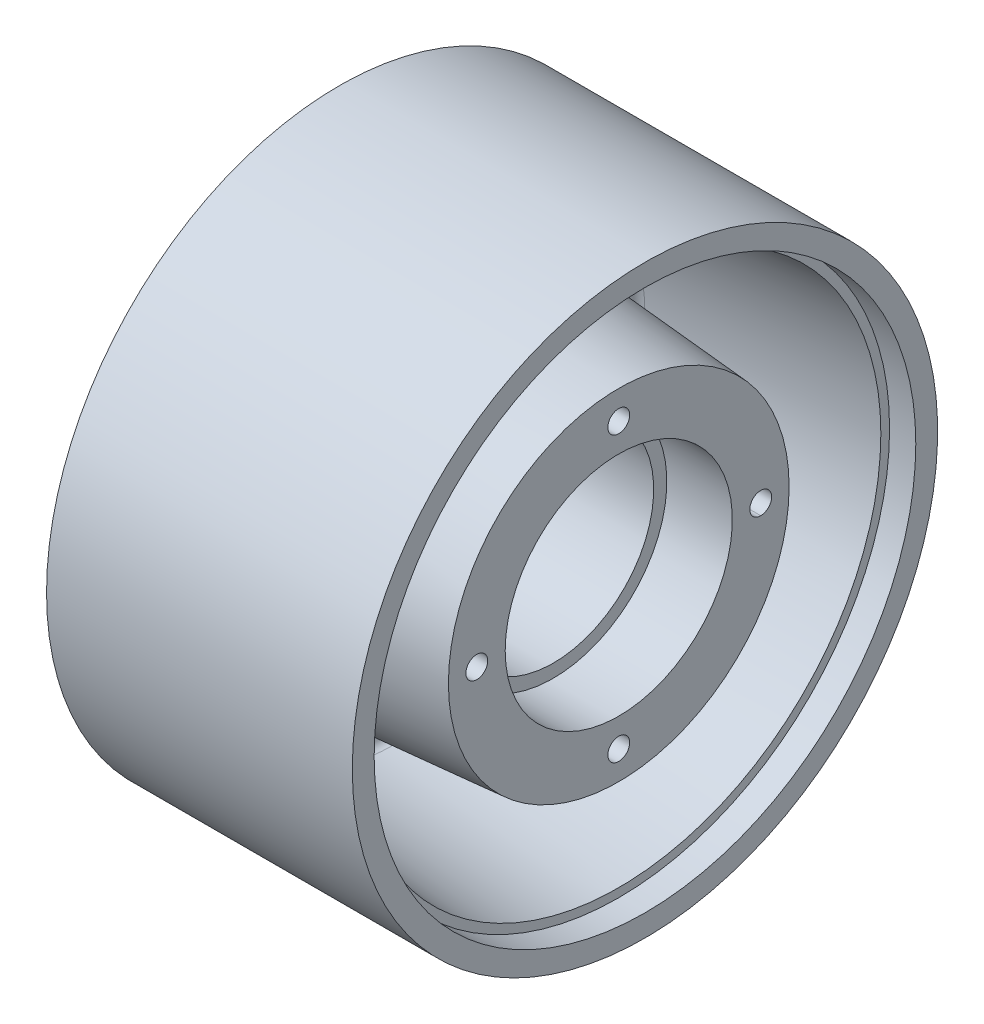
SolidWorks part; units mm, degrees
ref_plane "Alzado" through (0, 0, 0) normal (0, 0, 1) x (1, 0, 0)
ref_plane "Planta" through (0, 0, 0) normal (0, 1, 0) x (1, 0, 0)
ref_plane "Vista lateral" through (0, 0, 0) normal (1, 0, 0) x (0, 0, -1)
sketch "Croquis1" plane through (0, 0, 0) normal (0, 0, 1) x (1, 0, 0)
  line L0 (-33.5155, 0) -> (-7.5155, 0) construction
  line L18 (0, 67) -> (70, 67)
  line L19 (70, 67) -> (70, 62)
  line L20 (70, 62) -> (64, 62)
  line L21 (64, 62) -> (64, 60)
  line L22 (64, 60) -> (12, 56)
  line L23 (12, 56) -> (12, 43)
  line L24 (12, 43) -> (64, 39)
  line L25 (64, 39) -> (64, 26)
  line L27 (25, 26) -> (25, 23)
  line L28 (25, 23) -> (49, 23)
  line L29 (49, 23) -> (49, 26)
  line L31 (10, 26) -> (10, 40)
  line L32 (10, 40) -> (0, 40)
  line L33 (0, 40) -> (0, 67)
  line L34 (130.0302, 49.5) -> (-54.6416, 49.5) construction
  line L35 (10, 26) -> (25, 26)
  line L36 (49, 26) -> (64, 26)
  point P26 (-20.5155, 0)
  dimension "D1" = 67
  dimension "D2" = 62
  dimension "D3" = 60
  dimension "D4" = 15
  dimension "D5" = 23
  dimension "D6" = 15
  dimension "D7" = 70
  dimension "D8" = 6
  dimension "D9" = 54
  dimension "D10" = 12
  dimension "D11" = 40
  dimension "D12" = 3
  dimension "D13" = 39
  dimension "D14" = 13
  dimension "D15" = 3
revolve "Revolución1" add sketch "Croquis1" angle 360 about L0
fillet "Redondeo1" radius 2 2 edges at (12, 0, 43) (12, 0, 56)
hole_wizard "Taladro roscado M64" positions "Croquis15" profile "Croquis16" tap size "M6" standard "DIN"
sketch "Croquis15" plane through (64, 0, 0) normal (1, 0, 0) x (0, 0, -1)
  line L0 (0, 0) -> (0, 86.3628)
  circle A4 centre (0, 0) radius 32.5
  point P0 (0, 32.5)
sketch "Croquis16" plane through (64, 32.5, 0) normal (0, 1, 0) x (0, 0, -1)
  line L0 (0, 0) -> (0, 19.5022)
  line L1 (0, 19.5022) -> (2.5, 18)
  line L2 (2.5, 18) -> (2.5, 0)
  line L5 (2.5, 0) -> (0, 0)
  line L10 (0, 19.5022) -> (-2.5, 18) construction
  line L11 (0, -6.35) -> (0, 107.95) construction
  dimension "Diámetro de perforador para roscar" = 5
  dimension "Profundidad de perforador para roscar" = 18
  dimension "Ángulo de perforador" = 118
cosmetic thread "Rosca de taladro6" parameters "D1"=15, "D2"=6
hole_wizard "Taladro roscado M69" positions "Croquis25" profile "Croquis26" tap size "M6" standard "DIN"
sketch "Croquis25" plane through (64, 0, 0) normal (1, 0, 0) x (0, 0, -1)
  line L0 (0, 0) -> (0, -74.9026)
  circle A1 centre (0, 0) radius 32.5
  point P0 (0, -32.4706)
sketch "Croquis26" plane through (64, -32.4706, 0) normal (0, 1, 0) x (0, 0, -1)
  line L0 (0, 0) -> (0, 19.5022)
  line L1 (0, 19.5022) -> (2.5, 18)
  line L2 (2.5, 18) -> (2.5, 0)
  line L5 (2.5, 0) -> (0, 0)
  line L10 (0, 19.5022) -> (-2.5, 18) construction
  line L11 (0, -6.35) -> (0, 107.95) construction
  dimension "Diámetro de perforador para roscar" = 5
  dimension "Profundidad de perforador para roscar" = 18
  dimension "Ángulo de perforador" = 118
cosmetic thread "Rosca de taladro11" parameters "D1"=15, "D2"=6
hole_wizard "Taladro roscado M611" positions "Croquis29" profile "Croquis30" tap size "M6" standard "DIN"
sketch "Croquis29" plane through (10, 0, 0) normal (-1, 0, 0) x (0, 0, 1)
  line L0 (0, 0) -> (0, 69.3611)
  circle A0 centre (0, 0) radius 32.5
  point P0 (0, 32.4982)
sketch "Croquis30" plane through (10, 32.4982, 0) normal (0, 1, 0) x (0, 0, 1)
  line L0 (0, 0) -> (0, 16.5022)
  line L1 (0, 16.5022) -> (2.5, 15)
  line L2 (2.5, 15) -> (2.5, 0)
  line L5 (2.5, 0) -> (0, 0)
  line L10 (0, 16.5022) -> (-2.5, 15) construction
  line L11 (0, -6.35) -> (0, 107.95) construction
  dimension "Diámetro de perforador para roscar" = 5
  dimension "Profundidad de perforador para roscar" = 15
  dimension "Ángulo de perforador" = 118
cosmetic thread "Rosca de taladro13" parameters "D1"=12, "D2"=6
hole_wizard "Taladro roscado M612" positions "Croquis31" profile "Croquis32" tap size "M6" standard "DIN"
sketch "Croquis31" plane through (10, 0, 0) normal (-1, 0, 0) x (0, 0, 1)
  line L0 (0, 0) -> (0, -90.6399)
  circle A0 centre (0, 0) radius 32.5
  point P0 (0, -32.5002)
sketch "Croquis32" plane through (10, -32.5002, 0) normal (0, 1, 0) x (0, 0, 1)
  line L0 (0, 0) -> (0, 16.5022)
  line L1 (0, 16.5022) -> (2.5, 15)
  line L2 (2.5, 15) -> (2.5, 0)
  line L5 (2.5, 0) -> (0, 0)
  line L10 (0, 16.5022) -> (-2.5, 15) construction
  line L11 (0, -6.35) -> (0, 107.95) construction
  dimension "Diámetro de perforador para roscar" = 5
  dimension "Profundidad de perforador para roscar" = 15
  dimension "Ángulo de perforador" = 118
cosmetic thread "Rosca de taladro14" parameters "D1"=12, "D2"=6
hole_wizard "Taladro roscado M613" positions "Croquis33" profile "Croquis34" tap size "M6" standard "AS"
sketch "Croquis33" plane through (64, 0, 0) normal (1, 0, 0) x (0, 0, -1)
  line L0 (0, 0) -> (100.6706, 0)
  circle A0 centre (0, 0) radius 32.5
  point P0 (32.5017, 0)
sketch "Croquis34" plane through (64, 0, -32.5017) normal (0, 1, 0) x (0, 0, -1)
  line L0 (0, 0) -> (0, 19.5022)
  line L1 (0, 19.5022) -> (2.5, 18)
  line L2 (2.5, 18) -> (2.5, 0)
  line L5 (2.5, 0) -> (0, 0)
  line L10 (0, 19.5022) -> (-2.5, 18) construction
  line L11 (0, -6.35) -> (0, 107.95) construction
  dimension "Diámetro de perforador para roscar" = 5
  dimension "Profundidad de perforador para roscar" = 18
  dimension "Ángulo de perforador" = 118
cosmetic thread "Rosca de taladro15" parameters "D1"=15, "D2"=6
hole_wizard "Taladro roscado M614" positions "Croquis35" profile "Croquis36" tap size "M6" standard "DIN"
sketch "Croquis35" plane through (64, 0, 0) normal (1, 0, 0) x (0, 0, -1)
  line L0 (0, 0) -> (-107.9014, 0)
  circle A0 centre (0, 0) radius 32.5
  point P0 (32.5, 0)
  point P12 (-32.5, 0)
sketch "Croquis36" plane through (64, 0, -32.5) normal (0, 1, 0) x (0, 0, -1)
  line L0 (0, 0) -> (0, 19.5022)
  line L1 (0, 19.5022) -> (2.5, 18)
  line L2 (2.5, 18) -> (2.5, 0)
  line L5 (2.5, 0) -> (0, 0)
  line L10 (0, 19.5022) -> (-2.5, 18) construction
  line L11 (0, -6.35) -> (0, 107.95) construction
  dimension "Diámetro de perforador para roscar" = 5
  dimension "Profundidad de perforador para roscar" = 18
  dimension "Ángulo de perforador" = 118
cosmetic thread "Rosca de taladro16" parameters "D1"=15, "D2"=6
hole_wizard "Taladro roscado M615" positions "Croquis37" profile "Croquis38" tap size "M6" standard "DIN"
sketch "Croquis37" plane through (10, 0, 0) normal (-1, 0, 0) x (0, 0, 1)
  line L0 (0, 0) -> (86.8169, 0)
  line L1 (86.8169, 0) -> (-98.8234, 0)
  circle A0 centre (0, 0) radius 32.5
  point P0 (-32.4978, 0)
  point P2 (32.4975, 0)
sketch "Croquis38" plane through (10, 0, -32.4978) normal (0, 1, 0) x (0, 0, 1)
  line L0 (0, 0) -> (0, 16.5022)
  line L1 (0, 16.5022) -> (2.5, 15)
  line L2 (2.5, 15) -> (2.5, 0)
  line L5 (2.5, 0) -> (0, 0)
  line L10 (0, 16.5022) -> (-2.5, 15) construction
  line L11 (0, -6.35) -> (0, 107.95) construction
  dimension "Diámetro de perforador para roscar" = 5
  dimension "Profundidad de perforador para roscar" = 15
  dimension "Ángulo de perforador" = 118
cosmetic thread "Rosca de taladro17" parameters "D1"=12, "D2"=6
cosmetic thread "Rosca de taladro18" parameters "D1"=12, "D2"=6
sketch "Croquis39" plane through (64, 0, 0) normal (1, 0, 0) x (0, 0, -1)
  circle A1 centre (-32.5, 0) radius 3
  dimension "D1" = 6
